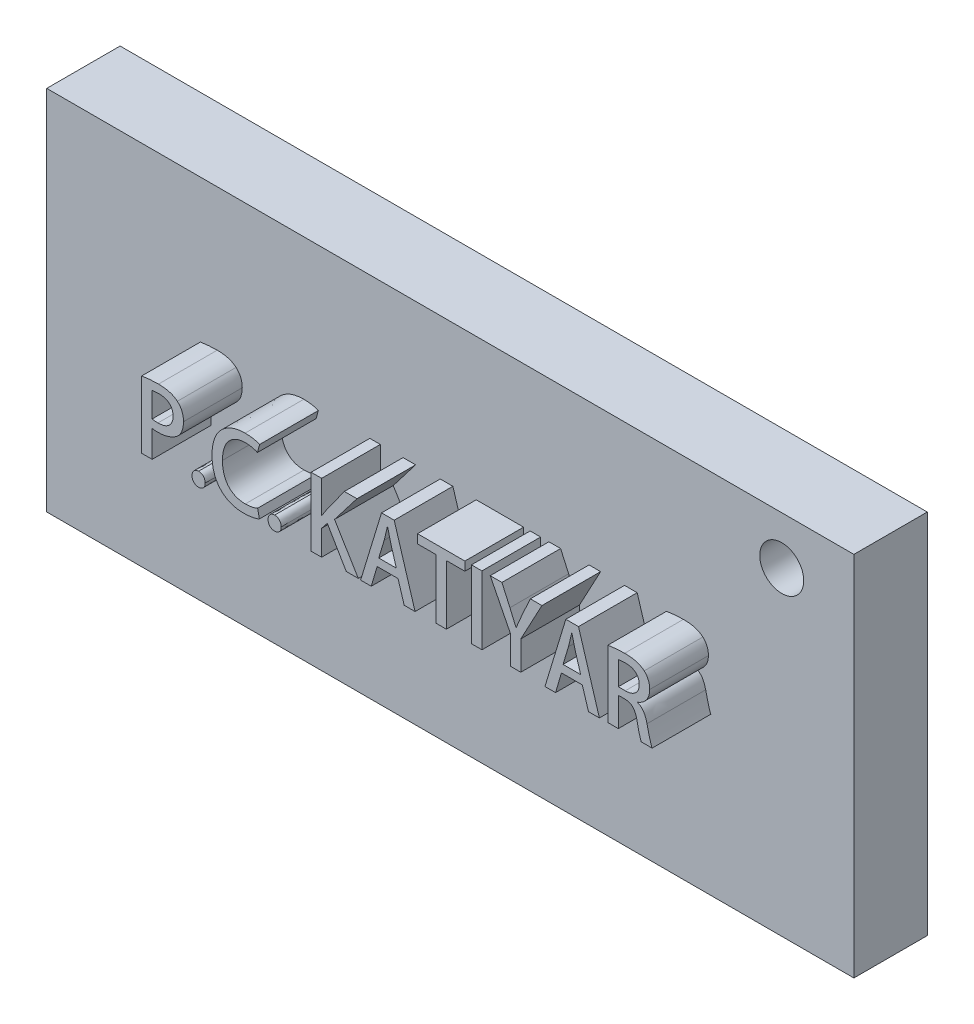
SolidWorks part; units mm, degrees
ref_plane "Front Plane" through (0, 0, 0) normal (0, 0, 1) x (1, 0, 0)
ref_plane "Top Plane" through (0, 0, 0) normal (0, 1, 0) x (1, 0, 0)
ref_plane "Right Plane" through (0, 0, 0) normal (1, 0, 0) x (0, 0, -1)
sketch "Sketch1" plane through (0, 0, 0) normal (0, 0, 1) x (1, 0, 0)
  line L1 (-27.5, -12.5) -> (27.5, -12.5)
  line L2 (-27.5, -12.5) -> (-27.5, 12.5)
  line L3 (-27.5, 12.5) -> (27.5, 12.5)
  line L4 (27.5, -12.5) -> (27.5, 12.5)
  line L5 (-27.5, -12.5) -> (27.5, 12.5) construction
  line L6 (-27.5, 12.5) -> (27.5, -12.5) construction
  point P0 (0, 0)
  dimension "D1" = 55
  dimension "D2" = 25
extrude "Boss-Extrude1" add sketch "Sketch1" along normal blind 5
sketch "Sketch3" plane through (0, 0, 5) normal (0, 0, 1) x (1, 0, 0)
  text T0 "                \r\nP.C. KATIYAR\r\n          " font "@Adobe Heiti Std R" height in points 15
extrude "Boss-Extrude4" add sketch "Sketch3" along normal blind 4
sketch "Sketch6" plane through (0, 0, 5) normal (0, 0, 1) x (1, 0, 0)
  circle A0 centre (22.5839, 9.234) radius 1.5
extrude "Cut-Extrude1" cut sketch "Sketch6" against normal blind 7
